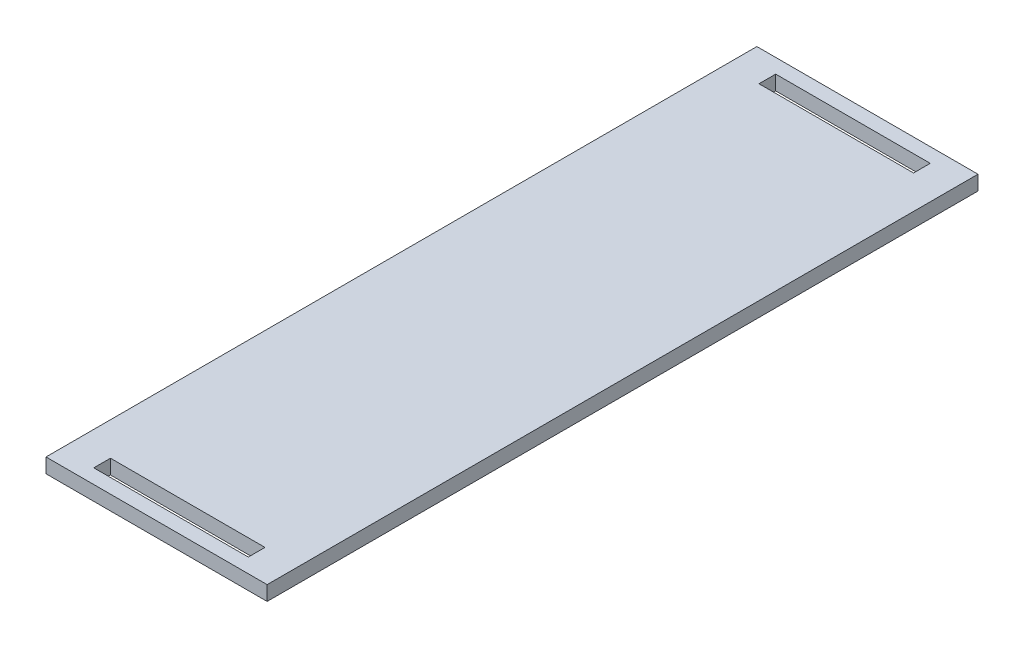
SolidWorks part; units mm, degrees
ref_plane "Front Plane" through (0, 0, 0) normal (0, 0, 1) x (1, 0, 0)
ref_plane "Top Plane" through (0, 0, 0) normal (0, 1, 0) x (1, 0, 0)
ref_plane "Right Plane" through (0, 0, 0) normal (1, 0, 0) x (0, 0, -1)
sketch "Sketch1" plane through (0, 0, 0) normal (0, 1, 0) x (1, 0, 0)
  line L0 (-22.7168, 66.4972) -> (22.7168, 66.4972) construction
  line L1 (22.7168, -73.025) -> (-22.7168, -73.025)
  line L2 (22.7168, -73.025) -> (22.7168, 73.025)
  line L3 (22.7168, 73.025) -> (-22.7168, 73.025)
  line L4 (-22.7168, -73.025) -> (-22.7168, 73.025)
  line L5 (22.7168, -73.025) -> (-22.7168, 73.025) construction
  line L6 (22.7168, 73.025) -> (-22.7168, -73.025) construction
  line L7 (-22.7168, -66.4972) -> (22.7168, -66.4972) construction
  line L8 (-22.7168, 66.4972) -> (-22.7168, -66.4972) construction
  line L9 (22.7168, 66.4972) -> (22.7168, -66.4972) construction
  line L10 (0, 66.6242) -> (0, -66.6242) construction
  line L11 (-15.875, 70.0532) -> (15.875, 70.0532)
  line L12 (-15.875, 70.0532) -> (-15.875, 66.6242)
  line L13 (-15.875, 66.6242) -> (15.875, 66.6242)
  line L14 (15.875, 70.0532) -> (15.875, 66.6242)
  line L15 (-15.875, -66.6242) -> (15.875, -66.6242)
  line L16 (-15.875, -66.6242) -> (-15.875, -70.0532)
  line L17 (-15.875, -70.0532) -> (15.875, -70.0532)
  line L18 (15.875, -66.6242) -> (15.875, -70.0532)
  line L19 (-22.7168, -70.0532) -> (22.7168, -70.0532) construction
  point P0 (0, 0)
  point P10 (22.7168, 0)
  point P11 (22.7168, 0)
  point P16 (0, 66.6242)
  point P17 (0, 0)
  dimension "D1" = 45.4337
  dimension "D2" = 146.05
  dimension "D3" = 132.9944
  dimension "D4" = 3.429
  dimension "D5" = 31.75
  dimension "D6" = 0.254
extrude "Boss-Extrude1" add sketch "Sketch1" along normal blind 2.9972 contours L4 L1 L2 L3 L11 L14 L13 L12 L15 L18 L17 L16
